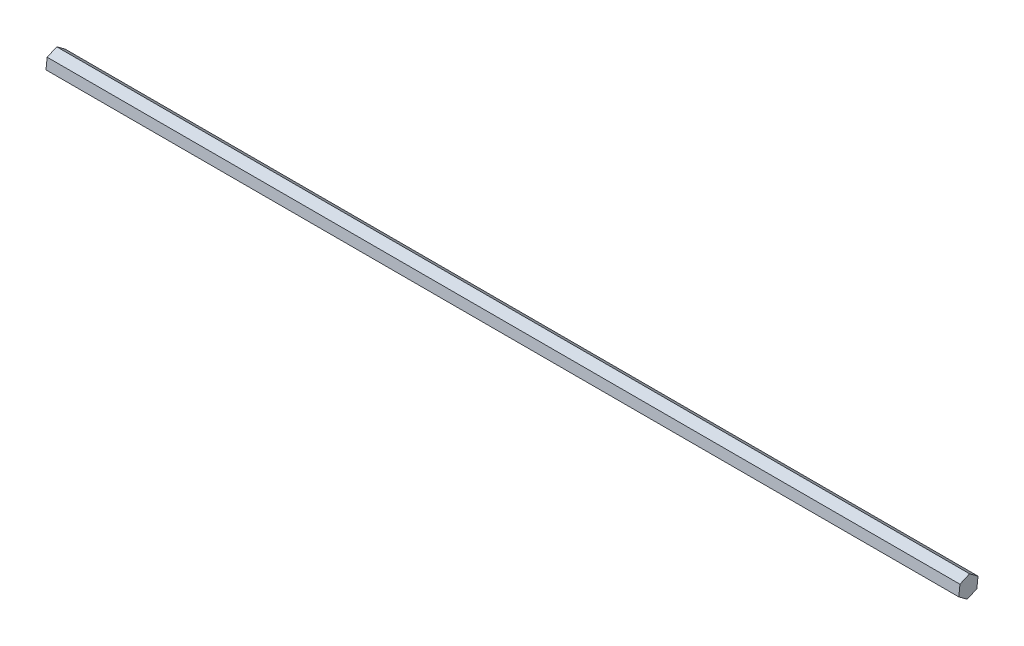
SolidWorks part; units mm, degrees
ref_plane "Front Plane" through (0, 0, 0) normal (0, 0, 1) x (1, 0, 0)
ref_plane "Top Plane" through (0, 0, 0) normal (0, 1, 0) x (1, 0, 0)
ref_plane "Right Plane" through (0, 0, 0) normal (1, 0, 0) x (0, 0, -1)
sketch "Sketch1" plane through (0, 0, 0) normal (1, 0, 0) x (0, 0, -1)
  line L1 (-0.6974, 0.5134) -> (-0.7934, -0.3473)
  line L2 (-0.7934, -0.3473) -> (-0.0959, -0.8607)
  line L3 (-0.0959, -0.8607) -> (0.6974, -0.5134)
  line L4 (0.6974, -0.5134) -> (0.7934, 0.3473)
  line L5 (0.7934, 0.3473) -> (0.0959, 0.8607)
  line L6 (0.0959, 0.8607) -> (-0.6974, 0.5134)
  circle A0 centre (0, 0) radius 0.75 construction
extrude "Boss-Extrude1" add sketch "Sketch1" along normal blind 50
sketch "Sketch2" plane through (0, 0, 0) normal (-1, 0, 0) x (0, 0, 1)
  line L1 (-0.7934, 0.3473) -> (-0.6974, -0.5134)
  line L2 (-0.6974, -0.5134) -> (0.0959, -0.8607)
  line L3 (0.0959, -0.8607) -> (0.7934, -0.3473)
  line L4 (0.7934, -0.3473) -> (0.6974, 0.5134)
  line L5 (0.6974, 0.5134) -> (-0.0959, 0.8607)
  line L6 (-0.0959, 0.8607) -> (-0.7934, 0.3473)
  circle A0 centre (0, 0) radius 0.75 construction
extrude "Boss-Extrude2" add sketch "Sketch2" along normal blind 25.4
